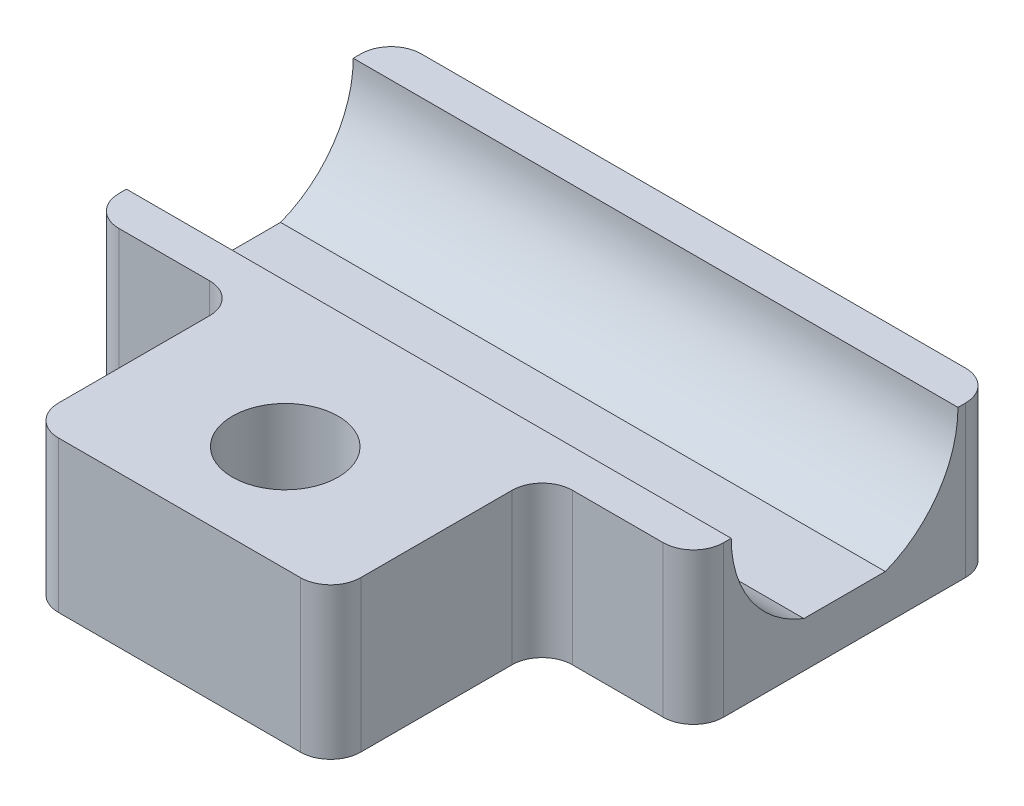
SolidWorks part; units mm, degrees
ref_plane "Front" through (0, 0, 0) normal (0, 0, 1) x (1, 0, 0)
ref_plane "Top" through (0, 0, 0) normal (0, 1, 0) x (1, 0, 0)
ref_plane "Right" through (0, 0, 0) normal (1, 0, 0) x (0, 0, -1)
sketch "Sketch1" plane through (0, 0, 0) normal (0, 1, 0) x (1, 0, 0)
  line L0 (-10, -10) -> (-20, -10)
  line L1 (20, -10) -> (10, -10)
  line L2 (20, -10) -> (20, 10)
  line L3 (20, 10) -> (-20, 10)
  line L4 (-20, -10) -> (-20, 10)
  line L5 (20, -10) -> (-20, 10) construction
  line L6 (20, 10) -> (-20, -10) construction
  line L8 (-10, -10) -> (-10, -24)
  line L9 (-10, -24) -> (10, -24)
  line L10 (10, -10) -> (10, -24)
  line L11 (0, -24) -> (0, -17) construction
  line L12 (-10, -17) -> (10, -17) construction
  point P0 (0, 0)
  point P222 (0, -17)
  dimension "D1" = 20
  dimension "D2" = 40
  dimension "D3" = 20
  dimension "D4" = 14
  dimension "D5" = 10
extrude "Boss-Extrude1" add sketch "Sketch1" along normal blind 10
sketch "Sketch2" plane through (0, 10, 0) normal (0, 1, 0) x (1, 0, 0)
  line L0 (-10, -24) -> (10, -24) construction
  line L1 (-10, -10) -> (-10, -24) construction
  circle A0 centre (0, -17) radius 3.5
  dimension "D1" = 7
  dimension "D2" = 7
  dimension "D3" = 10
extrude "Cut-Extrude1" cut sketch "Sketch2" against normal blind 10
sketch "Sketch3" plane through (20, 0, 0) normal (1, 0, 0) x (0, 0, -1)
  line L0 (-10, 10) -> (10, 10) construction
  line L1 (-2.6926, 3) -> (2.6926, 3)
  arc A0 (2.6926, 3) -> (-2.6926, 3) centre (0, 10) ccw
  dimension "D1" = 15
  dimension "D2" = 7
extrude "Cut-Extrude2" cut sketch "Sketch3" against normal through all
fillet "Fillet1" radius 2 8 edges at (-10, 5, 24) (-10, 5, 10) (-20, 5, 10) (-20, 5, -10) (20, 5, -10) (20, 5, 10) (10, 5, 10) (10, 5, 24)
